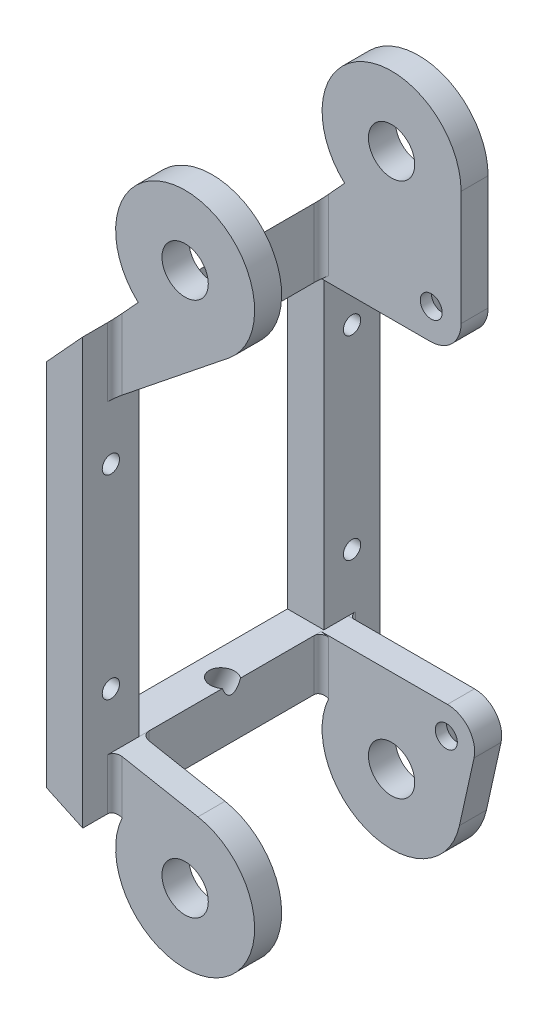
SolidWorks part; units mm, degrees
material "6061 Alloy"
ref_plane "Front Plane" through (0, 0, 0) normal (0, 0, 1) x (1, 0, 0)
ref_plane "Top Plane" through (0, 0, 0) normal (0, 1, 0) x (1, 0, 0)
ref_plane "Right Plane" through (0, 0, 0) normal (1, 0, 0) x (0, 0, -1)
sketch "Sketch2" plane through (0, 0, 0) normal (0, 0, 1) x (1, 0, 0)
  line L0 (240.1439, 163.4996) -> (228.1439, 151.3781)
  line L1 (240.1439, 163.4996) -> (240.1439, 204.2622)
  line L2 (240.1439, 204.2622) -> (228.1439, 206.3781)
  line L3 (228.1439, 151.3781) -> (216.1439, 156.9738)
  line L4 (216.1439, 193.2824) -> (228.1439, 206.3781)
  line L5 (216.1439, 193.2824) -> (216.1439, 156.9738)
  dimension "D16" = 12
extrude "link_geometry" add sketch "Sketch2" along normal blind 30.5723
sketch "Sketch3" plane through (0, 0, 30.5723) normal (0, 0, 1) x (1, 0, 0)
  circle A0 centre (228.1439, 151.3781) radius 7.1438
  circle A1 centre (228.1439, 206.3781) radius 7.1438
  dimension "D1" = 14.2875
  dimension "D2" = 14.2875
extrude "joint_rounds" add sketch "Sketch3" against normal up to surface (30.5723 mm away) up to face at (228.1439, 179.2957, 0)
sketch "Sketch5" plane through (0, 0, 30.5723) normal (0, 0, 1) x (1, 0, 0)
  circle A0 centre (228.1439, 206.3781) radius 2.3813
  circle A1 centre (228.1439, 151.3781) radius 2.3813
  dimension "D1" = 4.7625
  dimension "D2" = 4.7625
extrude "joint_holes" cut sketch "Sketch5" against normal through all
ref_plane "Plane1" through (0, 144.2344, 0) normal (0, -1, 0) x (-1, 0, 0)
sketch "Sketch6" plane through (0, 0, 30.5723) normal (0, 0, 1) x (1, 0, 0)
  line L0 (216.1439, 193.2824) -> (220.9064, 191.4304) construction
  line L1 (220.9064, 191.4304) -> (220.9064, 160.0079)
  line L2 (216.1439, 156.9738) -> (220.9064, 160.0079) construction
  line L3 (216.1439, 193.2824) -> (216.1439, 156.9738) construction
  line L6 (223.3176, 201.1112) -> (216.1439, 193.2824) construction
  line L7 (220.9064, 191.4304) -> (240.1439, 191.4304)
  line L8 (240.1439, 163.4996) -> (240.1439, 204.2622) construction
  line L10 (240.1439, 191.4304) -> (240.1439, 160.0079)
  line L13 (240.1439, 160.0079) -> (220.9064, 160.0079)
  circle A0 centre (228.1439, 206.3781) radius 7.1438 construction
  circle A1 centre (228.1439, 151.3781) radius 7.1438 construction
  arc A2 (221.6694, 154.3972) -> (233.1698, 156.4549) centre (228.1439, 151.3781) ccw construction
  dimension "D1" = 4.7625
  dimension "D2" = 122.5
  dimension "D3" = 111.25
extrude "bulk_removal" cut sketch "Sketch6" against normal through all
sketch "Sketch7" plane through (220.9064, 0, 0) normal (1, 0, 0) x (0, 0, -1)
  line L0 (-24.7861, 191.4304) -> (-5.7861, 191.4304)
  line L1 (0, 191.4304) -> (-30.5723, 191.4304) construction
  line L2 (0, 191.4304) -> (-30.5723, 191.4304) construction
  line L3 (-5.7861, 191.4304) -> (-5.7861, 160.0079)
  line L4 (0, 160.0079) -> (-30.5723, 160.0079) construction
  line L5 (-5.7861, 160.0079) -> (-24.7861, 160.0079)
  line L6 (0, 160.0079) -> (-30.5723, 160.0079) construction
  line L7 (-24.7861, 160.0079) -> (-24.7861, 191.4304)
  point P13 (-15.2861, 191.4304)
  point P14 (-15.2861, 191.4304)
  dimension "D1" = 19
extrude "contactpad_opening" cut sketch "Sketch7" against normal through all
sketch "Sketch9" plane through (0, 0, 30.5723) normal (0, 0, 1) x (1, 0, 0)
  circle A0 centre (228.1439, 151.3781) radius 7.3342
  circle A1 centre (228.1439, 206.3781) radius 7.3342
  dimension "D1" = 14.6685
extrude "Cut-Extrude4" cut sketch "Sketch9" against normal blind 3.2861
sketch "ref_tendon_mount" plane through (0, 0, 30.5723) normal (0, 0, 1) x (1, 0, 0)
  line L0 (216.1439, 156.9738) -> (221.4968, 154.4777) construction
  line L1 (217.2682, 156.4495) -> (219.5985, 161.4471) construction
  circle A0 centre (228.1439, 151.3781) radius 2.3813 construction
  point P0 (218.1446, 156.0409)
  dimension "D1" = 11.033
sketch "Sketch12" plane through (216.1439, 0, 0) normal (-1, 0, 0) x (0, 0, 1)
  line L1 (-11.4065, 145.784) -> (41.8615, 145.784)
  line L2 (-11.4065, 145.784) -> (-11.4065, 207.5522)
  line L3 (-11.4065, 207.5522) -> (41.8615, 207.5522)
  line L4 (41.8615, 145.784) -> (41.8615, 207.5522)
extrude "surface_reduction" cut sketch "Sketch12" against normal blind 1.016
hole_wizard "#2-56 Tapped Hole1" positions "Sketch16" profile "Sketch17" tap size "#2-56" standard "ANSI Inch" end condition through all
sketch "Sketch16" plane through (217.1599, 0, 0) normal (-1, 0, 0) x (0, 0, 1)
  line L0 (0, 194.3912) -> (0, 156.5) construction
  line L1 (5.7861, 191.4304) -> (5.7861, 160.0079) construction
  line L2 (24.7861, 160.0079) -> (24.7861, 191.4304) construction
  point P0 (2.8931, 185.7191)
  point P2 (2.8931, 165.7191)
  point P4 (27.6792, 165.7191)
  point P6 (27.6792, 185.7191)
  point P15 (5.7861, 175.7191)
  point P16 (24.7861, 175.7191)
  dimension "D1" = 20
  dimension "D2" = 2.8931
  dimension "D3" = 5.7861
  dimension "D4" = 2.8931
  dimension "D5" = 2.8931
  dimension "D6" = 2.8931
  dimension "D7" = 20
  dimension "D8" = 10
  dimension "D9" = 10
sketch "Sketch17" plane through (217.1599, 185.7191, 2.8931) normal (0, 1, 0) x (0, 0, 1)
  line L0 (0, 0) -> (0, 22.984)
  line L1 (0, 22.984) -> (0.889, 22.984)
  line L2 (0.889, 22.984) -> (0.889, 1.8532)
  line L3 (0.889, 1.8532) -> (2.5, 0)
  line L5 (2.5, 0) -> (0, 0)
  line L6 (-0.889, 1.8532) -> (-2.5, 0) construction
  line L11 (0, -6.35) -> (0, 107.95) construction
  dimension "Thread Major Dia." = 1.778
  dimension "Thru Tap Drill Depth" = 22.984
  dimension "Near C'Sink Dia." = 5
  dimension "Near C'Sink Angle" = 82
ref_plane "middle_plane" through (0, 0, 15.2861) normal (0, 0, 1) x (1, 0, 0)
sketch "Sketch19" plane through (0, 0, 15.2861) normal (0, 0, 1) x (1, 0, 0)
  circle A0 centre (228.1439, 206.3781) radius 7.3342
  circle A1 centre (228.1439, 151.3781) radius 7.3343
extrude "Cut-Extrude8" cut sketch "Sketch19" against normal mid plane 18.4438
sketch "Sketch20" plane through (0, 144.2344, 0) normal (0, -1, 0) x (-1, 0, 0)
  line L0 (-220.9064, -30.5723) -> (-220.9064, 0) construction
  line L1 (84306.3842, -30.5723) -> (-84743.2509, -30.5723) construction
  line L2 (-220.9064, -24.7861) -> (-220.9064, -30.5723) construction
  line L3 (-13.2, 0) -> (13.2, 0) construction
  line L4 (-220.9064, 0) -> (-220.9064, -5.7861) construction
  line L5 (-220.9064, -6.0643) -> (-242.2591, -6.0643)
  line L6 (-220.9064, -24.508) -> (-242.2591, -24.508)
  line L7 (-220.9064, -24.508) -> (-220.9064, -6.0643)
  line L8 (-242.2591, -6.0643) -> (-242.2591, -24.508)
  line L9 (-235.2876, -6.0643) -> (-221.0001, -6.0643) construction
  line L10 (-221.0001, -24.508) -> (-235.2876, -24.508) construction
extrude "Cut-Extrude9" cut sketch "Sketch20" against normal through all
sketch "Sketch21" plane through (0, 0, 27.2861) normal (0, 0, 1) x (1, 0, 0)
  line L0 (220.9064, 175.7191) -> (220.9064, 201.0747) construction
  line L2 (-84306.3842, -181105.1079) -> (84743.2509, 181423.0045) construction
  line L3 (220.9064, 144.8931) -> (245.0996, 144.8931)
  line L4 (220.9064, 144.8931) -> (220.9064, 216.1342)
  line L5 (220.9064, 216.1342) -> (245.0996, 216.1342)
  line L6 (245.0996, 144.8931) -> (245.0996, 216.1342)
extrude "Cut-Extrude10" cut sketch "Sketch21" along normal blind 18.4278
mirror "Mirror1" about plane through (0, 0, 15.2861) normal (0, 0, 1) of "Cut-Extrude10"
mirror "Mirror2" about plane through (0, 0, 15.2861) normal (0, 0, 1) of "Cut-Extrude4"
sketch "Sketch22" plane through (98.7291, 211.7252, 0) normal (-0.4226, -0.9063, 0) x (0.9063, -0.4226, 0)
  line L0 (131.7604, 30.5723) -> (131.7604, 0) construction
  line L1 (130.6739, 0) -> (134.8077, 0) construction
  circle A0 centre (131.7604, 15.2861) radius 0.535
  dimension "D1" = 1.07
extrude "Cut-Extrude12" cut sketch "Sketch22" against normal blind 18.4278
ref_plane "Plane3" through (99.4, 213.164, 0) normal (0.4226, 0.9063, 0) x (0.9063, -0.4226, 0)
sketch "Sketch23" plane through (99.4, 213.164, 0) normal (0.4226, 0.9063, 0) x (0.9063, -0.4226, 0)
  circle A0 centre (131.7604, -15.2861) radius 1.25
  dimension "D1" = 2.5
extrude "Cut-Extrude13" cut sketch "Sketch23" along normal blind 18.4278
ref_plane "Plane4" through (0, 175.7191, 0) normal (0, 1, 0) x (1, 0, 0)
sketch "Sketch25" plane through (0, 0, 3.2861) normal (0, 0, -1) x (-1, 0, 0)
  line L0 (-220.9064, 160.0079) -> (-229.4639, 158.3989)
  line L1 (-220.9064, 191.4304) -> (-232.6092, 200.8019)
  line L2 (-233.1698, 156.4549) -> (-246.03, 156.4549)
  line L3 (-246.03, 156.4549) -> (-246.03, 205.1376)
  line L4 (-246.03, 205.1376) -> (-235.1791, 205.1376)
  line L5 (-220.9064, 160.0079) -> (-220.9064, 191.4304)
  arc A0 (-233.1698, 156.4549) -> (-229.4639, 158.3989) centre (-228.1439, 151.3781) cw
  arc A1 (-235.1791, 205.1376) -> (-232.6092, 200.8019) centre (-228.1439, 206.3781) ccw
extrude "Cut-Extrude14" cut sketch "Sketch25" against normal through all
fillet "Fillet1" radius 0.75 8 edges at (220.9064, 194.9551, 3.2861) (220.9064, 157.3804, 24.508) (220.9064, 157.3804, 6.0643) (220.9064, 157.3804, 3.2861) (220.9064, 157.3804, 27.2861) (220.9064, 194.9551, 24.508) (220.9064, 194.9551, 6.0643) (220.9064, 194.9551, 27.2861)
sketch "Sketch26" plane through (0, 0, 3.2861) normal (0, 0, -1) x (-1, 0, 0)
  line L1 (-220.9064, 160.0079) -> (-235.2876, 160.0079)
  line L2 (-220.9064, 160.0079) -> (-229.4639, 158.3989)
  line L3 (-235.2876, 160.0079) -> (-237.3742, 160.0079)
  line L4 (-235.1183, 149.8319) -> (-237.3742, 160.0079)
  line L6 (-220.9064, 191.4304) -> (-232.6092, 200.8019)
  line L7 (-235.2876, 206.3779) -> (-235.2872, 191.43)
  line L8 (-235.2872, 191.43) -> (-220.9064, 191.4304)
  arc A0 (-229.4639, 158.3989) -> (-221.6694, 154.3972) centre (-228.1439, 151.3781) ccw construction
  arc A1 (-223.3176, 201.1112) -> (-232.6092, 200.8019) centre (-228.1439, 206.3781) ccw construction
  arc A3 (-235.1183, 149.8319) -> (-229.4639, 158.3989) centre (-228.1439, 151.3781) cw
  arc A4 (-235.2876, 206.3779) -> (-232.6092, 200.8019) centre (-228.1439, 206.3781) ccw
  dimension "D1" = 77.5
  dimension "D2" = 90
extrude "Boss-Extrude1" add sketch "Sketch26" against normal up to surface (2.7781 mm away) up to face at (225.0715, 153.9228, 6.0643)
sketch "Sketch28" plane through (0, 0, 3.2861) normal (0, 0, -1) x (-1, 0, 0)
  line L0 (-232.6397, 151.3781) -> (-232.6397, 160.0079) construction
  line L1 (-220.9064, 160.0079) -> (-237.3742, 160.0079) construction
  line L2 (-230.1994, 191.4301) -> (-233.799, 204.8627) construction
  line L3 (-235.2872, 191.43) -> (-220.9064, 191.4304) construction
  line L4 (-235.2876, 206.3779) -> (-235.2872, 191.43) construction
  circle A0 centre (-228.1439, 151.3781) radius 4.4958 construction
  circle A1 centre (-233.77, 157.1281) radius 1.1303
  circle A2 centre (-228.1439, 206.3781) radius 5.8547 construction
  circle A3 centre (-232.2204, 194.6051) radius 1.1303
  dimension "D1" = 8.9916
  dimension "D2" = 2.2606
  dimension "D4" = 11.7094
  dimension "D3" = 5.75
  dimension "D5" = 15
  dimension "D6" = 3.175
extrude "prox_spring_hole" cut sketch "Sketch28" against normal up to surface (2.7781 mm away) up to face at (225.9725, 155.169, 6.0643)
fillet "Fillet2" radius 2.8 1 edges at (237.3742, 160.0079, 4.6752)
hole_wizard "CSK for #2 Flat Head Machine Screw1" positions "Sketch29" profile "Sketch30" countersink size "#2" standard "ANSI Inch"
sketch "Sketch29" plane through (0, 0, 3.2861) normal (0, 0, -1) x (-1, 0, 0)
  point P0 (-233.77, 157.1281)
  point P3 (-232.2204, 194.6051)
sketch "Sketch30" plane through (233.77, 157.1281, 3.2861) normal (1, 0, 0) x (0, 1, 0)
  line L0 (0, 0) -> (0, 3.4563)
  line L1 (0, 3.4563) -> (1.1303, 2.7771)
  line L2 (1.1303, 2.7771) -> (1.1303, 1.6332)
  line L3 (1.1303, 1.6332) -> (2.55, 0)
  line L5 (2.55, 0) -> (0, 0)
  line L6 (-1.1303, 1.6332) -> (-2.55, 0) construction
  line L10 (0, 3.4563) -> (-1.1303, 2.7771) construction
  line L11 (0, -6.35) -> (0, 107.95) construction
  dimension "Hole Dia." = 2.2606
  dimension "Hole Depth" = 2.7771
  dimension "Near C'Sink Dia." = 5.1
  dimension "Near C'Sink Angle" = 82
  dimension "Drill Angle" = 118
sketch "Sketch31" plane through (0, 0, 30.5723) normal (0, 0, 1) x (1, 0, 0)
  circle A0 centre (228.1439, 206.3781) radius 2.3813 construction
  point P0 (219.1439, 193.6281)
  dimension "D1" = 12.75
  dimension "D2" = 9
ref_plane "Plane5" through (22.6761, -20.7788, 0) normal (-0.7373, 0.6756, 0) x (0, 0, 1)
sketch "Sketch32" plane through (22.6761, -20.7788, 0) normal (-0.7373, 0.6756, 0) x (0, 0, 1)
  line L0 (30.5723, 290.8091) -> (0, 290.8091) construction
  line L1 (0, 295.5768) -> (0, 290.0313) construction
  circle A0 centre (15.2861, 290.8091) radius 1.025
  dimension "D1" = 2.05
extrude "distal_sheath_hole" cut sketch "Sketch32" against normal blind 19.05
sketch "Sketch33" plane through (22.6761, -20.7788, 0) normal (0.7373, -0.6756, 0) x (0, 0, -1)
  line L0 (-15.2861, 291.0671) -> (-15.2861, -49708.9329) construction
  line L1 (-15.9361, 297.1591) -> (-15.9361, 284.4591)
  line L2 (-14.6361, 297.1591) -> (-14.6361, 284.4591)
  arc A0 (-14.6361, 297.1591) -> (-15.9361, 297.1591) centre (-15.2861, 297.1591) ccw
  arc A1 (-15.9361, 284.4591) -> (-14.6361, 284.4591) centre (-15.2861, 284.4591) ccw
  arc A2 (-14.3555, 290.3795) -> (-16.2167, 290.3795) centre (-15.2861, 290.8091) ccw construction
  dimension "D1" = 1.3
  dimension "D2" = 12.7
  dimension "D3" = 6.35
extrude "distal_sheath_slot" cut sketch "Sketch33" against normal blind 19.05
fillet "Fillet3" radius 3.175 1 edges at (235.2872, 191.43, 4.6752)
equation "\"D2@Sketch16\"=\"D3@Sketch16\"/2"
equation "\"D4@Sketch16\"=\"D2@Sketch16\""
equation "\"D5@Sketch16\"=\"D2@Sketch16\""
equation "\"D6@Sketch16\"=\"D2@Sketch16\""
equation "\"D7@Sketch16\"=\"D1@Sketch16\""
equation "\"D8@Sketch16\"=\"D1@Sketch16\"/2"
equation "\"D9@Sketch16\"=\"D8@Sketch16\""
equation "\"D3@Sketch33\"=0.5*\"D2@Sketch33\""
